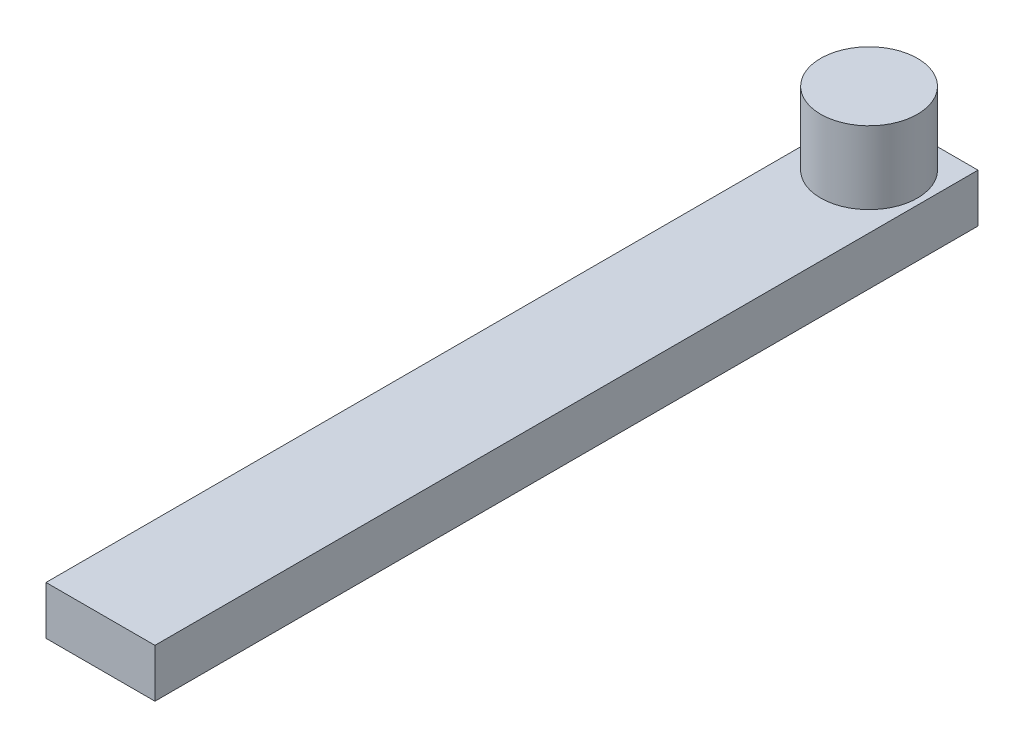
SolidWorks part; units mm, degrees
material "Hierro dúctil"
ref_plane "Alzado" through (0, 0, 0) normal (0, 0, 1) x (1, 0, 0)
ref_plane "Planta" through (0, 0, 0) normal (0, 1, 0) x (1, 0, 0)
ref_plane "Vista lateral" through (0, 0, 0) normal (1, 0, 0) x (0, 0, -1)
sketch "Croquis1" plane through (0, 0, 0) normal (0, 1, 0) x (1, 0, 0)
  line L0 (0, 60) -> (0, 400)
  line L1 (0, 400) -> (45, 400)
  line L2 (45, 400) -> (45, 60)
  line L3 (45, 60) -> (0, 60)
  dimension "D1" = 45
  dimension "D2" = 340
extrude "Saliente-Extruir1" add sketch "Croquis1" along normal blind 20
sketch "Croquis2" plane through (0, 20, 0) normal (0, 1, 0) x (1, 0, 0)
  line L0 (0, 400) -> (45, 355)
  line L1 (45, 400) -> (45, 60) construction
  line L2 (45, 355) -> (0, 355)
  line L3 (0, 60) -> (0, 400) construction
  line L4 (0, 355) -> (45, 400)
  line L5 (0, 400) -> (45, 400) construction
  circle A0 centre (22.5, 377.5) radius 20
  line M1 (0, 400) -> (0, 60)
  line M7 (45, 60) -> (45, 400)
  line M8 (45, 400) -> (0, 400)
  dimension "D1" = 45
extrude "Saliente-Extruir2" add sketch "Croquis2" along normal blind 30 contours L2 A0 L0 L4 | L0 A0 L4 M1 | L4 A0 L0 M8 | L0 A0 L4 M7 | A0 M7 | A0 M8 | A0 M1
